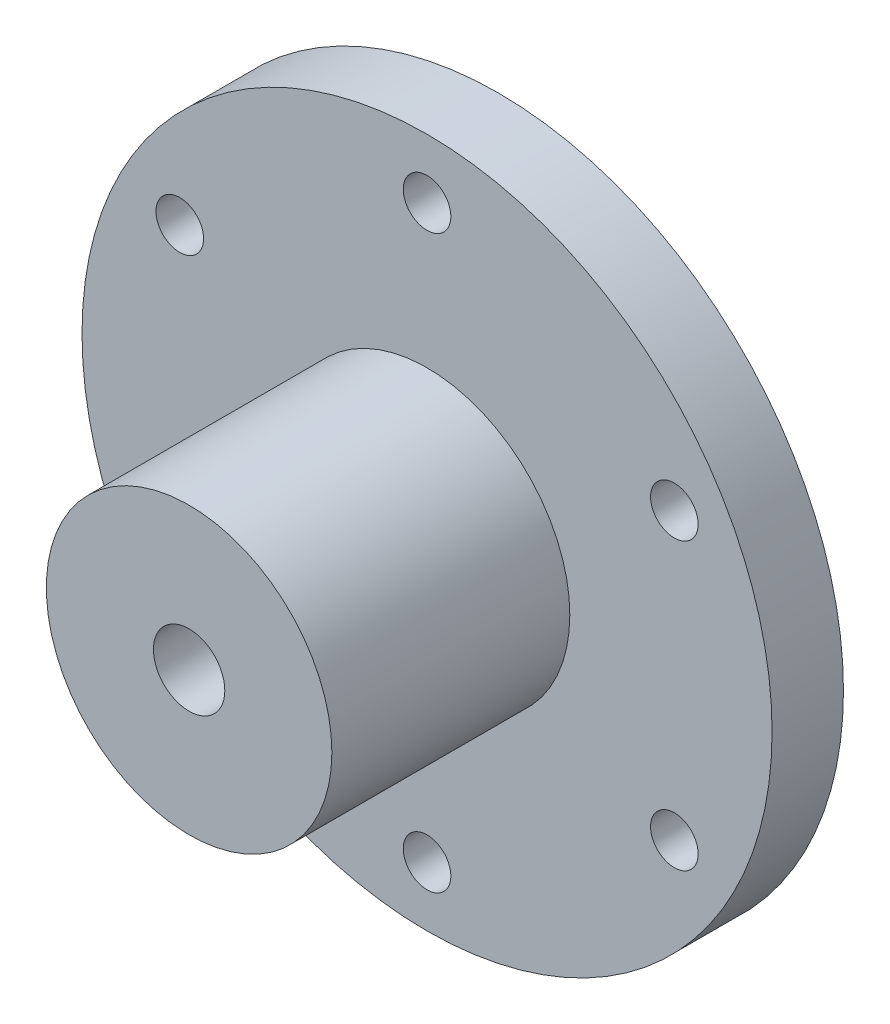
SolidWorks part; units mm, degrees
ref_plane "前视基准面" through (0, 0, 0) normal (0, 0, 1) x (1, 0, 0)
ref_plane "上视基准面" through (0, 0, 0) normal (0, 1, 0) x (1, 0, 0)
ref_plane "右视基准面" through (0, 0, 0) normal (1, 0, 0) x (0, 0, -1)
sketch "草图1" plane through (0, 0, 0) normal (0, 0, 1) x (1, 0, 0)
  circle A0 centre (0, 0) radius 29
extrude "凸台-拉伸1" add sketch "草图1" along normal blind 6 contours A0
sketch "草图2" plane through (0, 0, 6) normal (0, 0, 1) x (1, 0, 0)
  circle A0 centre (0, 0) radius 12
extrude "凸台-拉伸2" add sketch "草图2" along normal blind 20
sketch "草图3" plane through (0, 0, 6) normal (0, 0, 1) x (1, 0, 0)
  circle A1 centre (0, 24) radius 2
  circle A2 centre (20.7846, 12) radius 2
  circle A3 centre (20.7846, -12) radius 2
  circle A4 centre (0, -24) radius 2
  circle A5 centre (-20.7846, -12) radius 2
  circle A6 centre (-20.7846, 12) radius 2
  point P17 (0, 0)
  dimension "D1" = 6
extrude "切除-拉伸1" cut sketch "草图3" against normal blind 10
sketch "草图4" plane through (0, 0, 26) normal (0, 0, 1) x (1, 0, 0)
  circle A0 centre (0, 0) radius 3
extrude "切除-拉伸2" cut sketch "草图4" against normal blind 30 contours A0
move or copy body "实体-移动/复制1" [suppressed] bodies to move or copy 109
